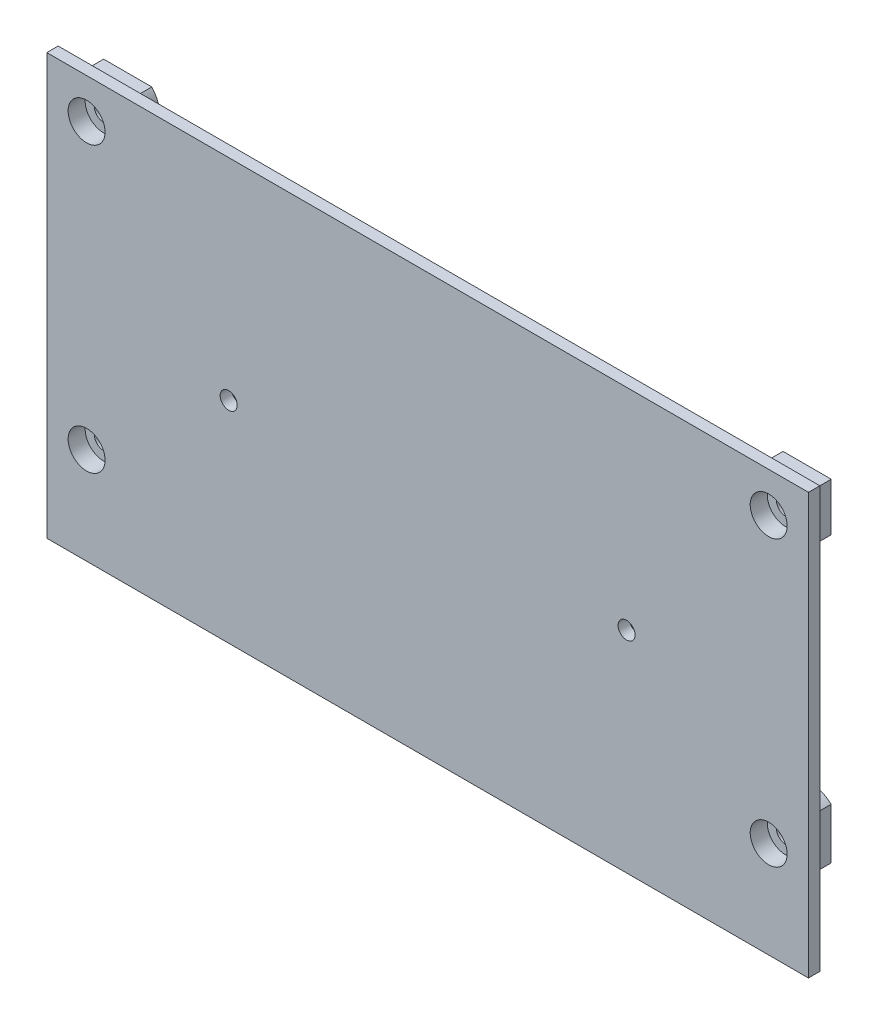
SolidWorks part; units mm, degrees
material "ABS"
ref_plane "Plano frontal" through (0, 0, 0) normal (0, 0, 1) x (1, 0, 0)
ref_plane "Plano superior" through (0, 0, 0) normal (0, 1, 0) x (1, 0, 0)
ref_plane "Plano direito" through (0, 0, 0) normal (1, 0, 0) x (0, 0, -1)
sketch "Esboço1" plane through (0, 0, 0) normal (0, 0, 1) x (1, 0, 0)
  line L0 (0, 0) -> (134, 0)
  line L1 (32, -37) -> (102, -37) construction
  line L2 (134, -74) -> (0, -74)
  line L3 (0, -74) -> (0, 0)
  line L5 (7, -57) -> (127, -57) construction
  line L6 (134, 0) -> (134, -74)
  line L7 (7, -57) -> (7, -7) construction
  line L8 (7, -7) -> (127, -7) construction
  line L9 (127, -57) -> (127, -7) construction
  line L10 (7, -57) -> (127, -7) construction
  line L11 (7, -7) -> (127, -57) construction
  circle A0 centre (102, -37) radius 1.5
  circle A1 centre (7, -7) radius 1.65
  circle A2 centre (127, -7) radius 1.65
  circle A3 centre (127, -57) radius 1.65
  circle A4 centre (7, -57) radius 1.65
  circle A6 centre (32, -37) radius 1.5
  point P5 (67, -37)
  point P6 (67, 0)
  point P8 (67, -37)
  point P26 (0, -37)
  dimension "D10" = 3
  dimension "D3" = 3.3
  dimension "D5" = 134
  dimension "D6" = 74
  dimension "D2" = 70
  dimension "D4" = 7
  dimension "D7" = 7
  dimension "D8" = 50
  dimension "D9" = 7
extrude "Ressalto-extrusão1" add sketch "Esboço1" along normal blind 2
sketch "Esboço2" plane through (0, 0, 0) normal (0, 0, -1) x (-1, 0, 0)
  line L0 (0, -74) -> (-134, -74) construction
  line L2 (-3, -61.4721) -> (-3, -52.5279)
  line L3 (-3, -3) -> (-11.4721, -3)
  line L4 (-131, -61.4721) -> (-131, -52.5279)
  line L5 (-3, -61.4721) -> (-131, -3) construction
  line L6 (-3, -3) -> (-131, -61.4721) construction
  line L7 (0, 0) -> (0, -74) construction
  line L9 (-134, 0) -> (0, 0) construction
  line L10 (-131, -11.4721) -> (-131, -3)
  line L11 (-122.5279, -3) -> (-131, -3)
  line L13 (-3, -11.4721) -> (-3, -3)
  line L15 (-134, -74) -> (-134, 0) construction
  circle A0 centre (-102, -37) radius 6
  circle A1 centre (-32, -37) radius 6
  arc A2 (-11.4721, -3) -> (-3, -11.4721) centre (-7, -7) ccw
  arc A3 (-3, -52.5279) -> (-3, -61.4721) centre (-7, -57) ccw
  arc A4 (-131, -11.4721) -> (-122.5279, -3) centre (-127, -7) ccw
  arc A5 (-131, -61.4721) -> (-131, -52.5279) centre (-127, -57) ccw
  circle A6 centre (-127, -7) radius 1.65
  circle A7 centre (-7, -7) radius 1.65
  circle A8 centre (-7, -57) radius 1.65
  circle A9 centre (-127, -57) radius 1.65
  circle A10 centre (-102, -37) radius 1.5
  circle A11 centre (-32, -37) radius 1.5
  point P0 (-67, -37)
  point P2 (0, 0)
  point P9 (-67, -74)
  point P13 (0, -37)
  point P43 (0, 0)
  point P44 (0, 0)
  point P45 (-125.0232, -62.665)
  point P46 (0, 0)
  dimension "D3" = 6
  dimension "D4" = 3.3
  dimension "D5" = 12
  dimension "D6" = 3
  dimension "D2" = 3
  dimension "D1" = 3
  dimension "D7" = 3
extrude "Ressalto-extrusão2" add sketch "Esboço2" along normal blind 5
sketch "Esboço3" plane through (0, 0, 2) normal (0, 0, 1) x (1, 0, 0)
  circle A0 centre (7, -7) radius 3.25
  circle A1 centre (32, -37) radius 3.25 construction
  circle A2 centre (7, -57) radius 3.25
  circle A3 centre (102, -37) radius 3.25 construction
  circle A4 centre (127, -7) radius 3.25
  circle A5 centre (127, -57) radius 3.25
  dimension "D1" = 6.5
extrude "Corte-extrusão1" cut sketch "Esboço3" against normal blind 3
sketch "Esboço4" plane through (0, 0, -5) normal (0, 0, -1) x (-1, 0, 0)
  line L1 (-34.0207, -40.5) -> (-29.9793, -40.5)
  line L2 (-29.9793, -40.5) -> (-27.9585, -37)
  line L3 (-27.9585, -37) -> (-29.9793, -33.5)
  line L4 (-29.9793, -33.5) -> (-34.0207, -33.5)
  line L5 (-34.0207, -33.5) -> (-36.0415, -37)
  line L6 (-36.0415, -37) -> (-34.0207, -40.5)
  line L7 (-97.9585, -37) -> (-99.9793, -33.5)
  line L8 (-99.9793, -33.5) -> (-104.0207, -33.5)
  line L9 (-104.0207, -33.5) -> (-106.0415, -37)
  line L10 (-106.0415, -37) -> (-104.0207, -40.5)
  line L11 (-104.0207, -40.5) -> (-99.9793, -40.5)
  line L12 (-99.9793, -40.5) -> (-97.9585, -37)
  circle A0 centre (-32, -37) radius 3.5 construction
  circle A1 centre (-102, -37) radius 3.5 construction
  point P10 (-27.9585, -37)
  point P19 (0, 0)
  dimension "D1" = 7
extrude "Corte-extrusão2" cut sketch "Esboço4" against normal blind 5 draft 12
equation "\"D7@Esboço1\"=\"D4@Esboço1\""
equation "\"D9@Esboço1\"=\"D4@Esboço1\""
equation "\"D1@Esboço2\"=\"D2@Esboço2\""
equation "\"D7@Esboço2\"=\"D2@Esboço2\""
